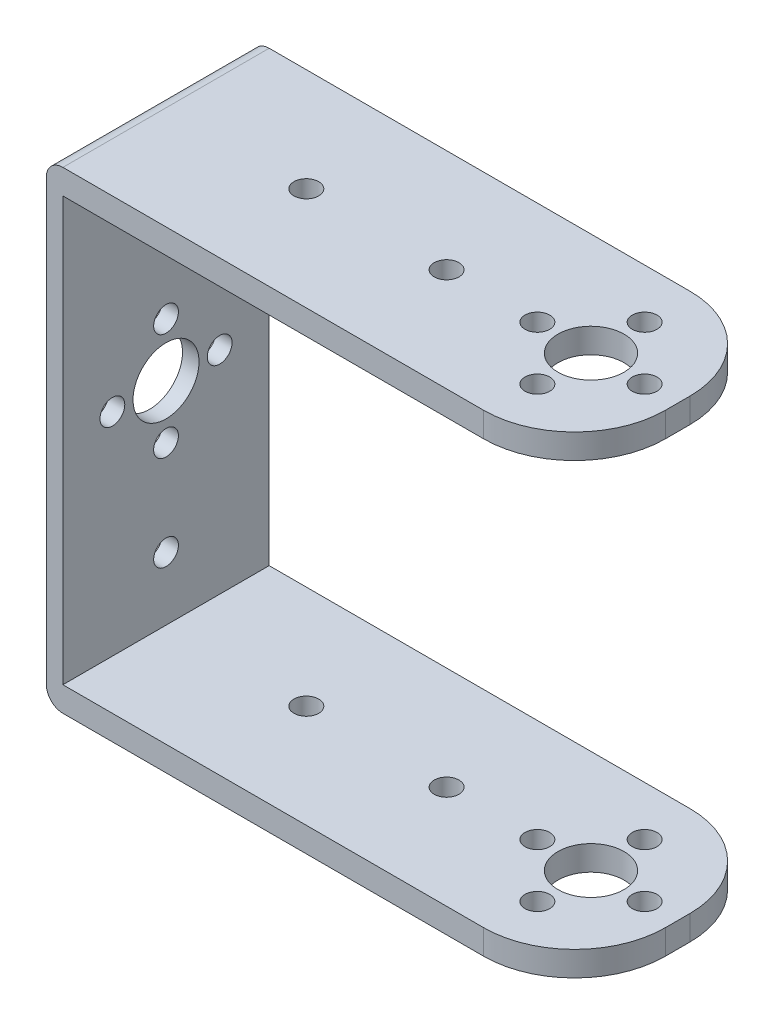
SolidWorks part; units mm, degrees
ref_plane "Front Plane" through (0, 0, 0) normal (0, 0, 1) x (1, 0, 0)
ref_plane "Top Plane" through (0, 0, 0) normal (0, 1, 0) x (1, 0, 0)
ref_plane "Right Plane" through (0, 0, 0) normal (1, 0, 0) x (0, 0, -1)
sketch "Sketch1" plane through (0, 0, 0) normal (0, 1, 0) x (1, 0, 0)
  line L1 (0, 0) -> (64, 0)
  line L2 (0, 0) -> (0, 25)
  line L3 (0, 25) -> (64, 25)
  line L4 (64, 0) -> (64, 25)
  dimension "D1" = 64
  dimension "D2" = 25
extrude "Boss-Extrude1" add sketch "Sketch1" along normal blind 56.3 and the other way blind 1
sketch "Sketch3" plane through (0, 0, 0) normal (0, 0, 1) x (1, 0, 0)
  line L0 (64, 56.3) -> (64, -1) construction
  line L1 (2, 53.3) -> (64, 53.3)
  line L2 (2, 53.3) -> (2, 2)
  line L3 (2, 2) -> (64, 2)
  line L4 (64, 53.3) -> (64, 2)
  line L5 (0, 56.3) -> (64, 56.3) construction
  line L6 (0, -1) -> (64, -1) construction
  line L7 (0, 56.3) -> (0, -1) construction
  dimension "D1" = 3
  dimension "D2" = 3
  dimension "2" = 2
extrude "Cut-Extrude2" cut sketch "Sketch3" against normal through all
sketch "Sketch4" plane through (2, 0, 0) normal (1, 0, 0) x (0, 0, -1)
  line L0 (0, 27.65) -> (25, 27.65) construction
  line L1 (0, 53.3) -> (0, 2) construction
  line L2 (25, 53.3) -> (25, 2) construction
  line L3 (12.5, 27.65) -> (12.5, 53.3) construction
  line L4 (25, 53.3) -> (0, 53.3) construction
  circle A0 centre (12.5, 27.65) radius 4
  circle A1 centre (19, 27.65) radius 1.5
  circle A2 centre (12.5, 34.15) radius 1.5
  circle A3 centre (6, 27.65) radius 1.5
  circle A4 centre (12.5, 21.15) radius 1.5
  dimension "D1" = 8
  dimension "D2" = 3
  dimension "D3" = 3
  dimension "D4" = 6.5
  dimension "D5" = 6.5
extrude "Cut-Extrude3" cut sketch "Sketch4" against normal blind 56
sketch "Sketch8" plane through (2, 0, 0) normal (1, 0, 0) x (0, 0, -1)
  circle A0 centre (12.5, 45.65) radius 1.5
  circle A1 centre (12.5, 27.65) radius 4 construction
  circle A2 centre (12.5, 9.65) radius 1.5
  dimension "D1" = 3
  dimension "D2" = 18
  dimension "D3" = 18
  dimension "3" = 3
extrude "Cut-Extrude4" cut sketch "Sketch8" against normal blind 56
fillet "Fillet1" radius 2 2 edges at (0, 56.3, -12.5) (0, -1, -12.5)
sketch "Sketch9" plane through (0, 56.3, 0) normal (0, 1, 0) x (1, 0, 0)
  line L0 (64, 0) -> (64, 25) construction
  circle A0 centre (60, 12.5) radius 1.5
  circle A1 centre (53.5, 12.5) radius 4
  circle A2 centre (53.5, 19) radius 1.5
  circle A3 centre (47, 12.5) radius 1.5
  circle A4 centre (53.5, 6) radius 1.5
  dimension "D1" = 4
  dimension "3" = 3
  dimension "D2" = 8
  dimension "D4" = 3
  dimension "D5" = 3
  dimension "D6" = 3
  dimension "D9" = 6.5
  dimension "D3" = 6.5
  dimension "D7" = 6.5
  dimension "D8" = 6.5
extrude "Cut-Extrude5" cut sketch "Sketch9" against normal through all
fillet "Fillet3" radius 11 4 edges at (64, 0.5, -25) (64, 0.5, 0) (64, 54.8, 0) (64, 54.8, -25)
sketch "Sketch10" plane through (0, 56.3, 0) normal (0, 1, 0) x (1, 0, 0)
  circle A0 centre (36, 12.5) radius 1.5
  circle A1 centre (47, 12.5) radius 1.5 construction
  circle A2 centre (19, 12.5) radius 1.5
  dimension "D1" = 3
  dimension "D2" = 11
  dimension "D3" = 17
  dimension "3" = 3
extrude "Cut-Extrude6" cut sketch "Sketch10" against normal through all
